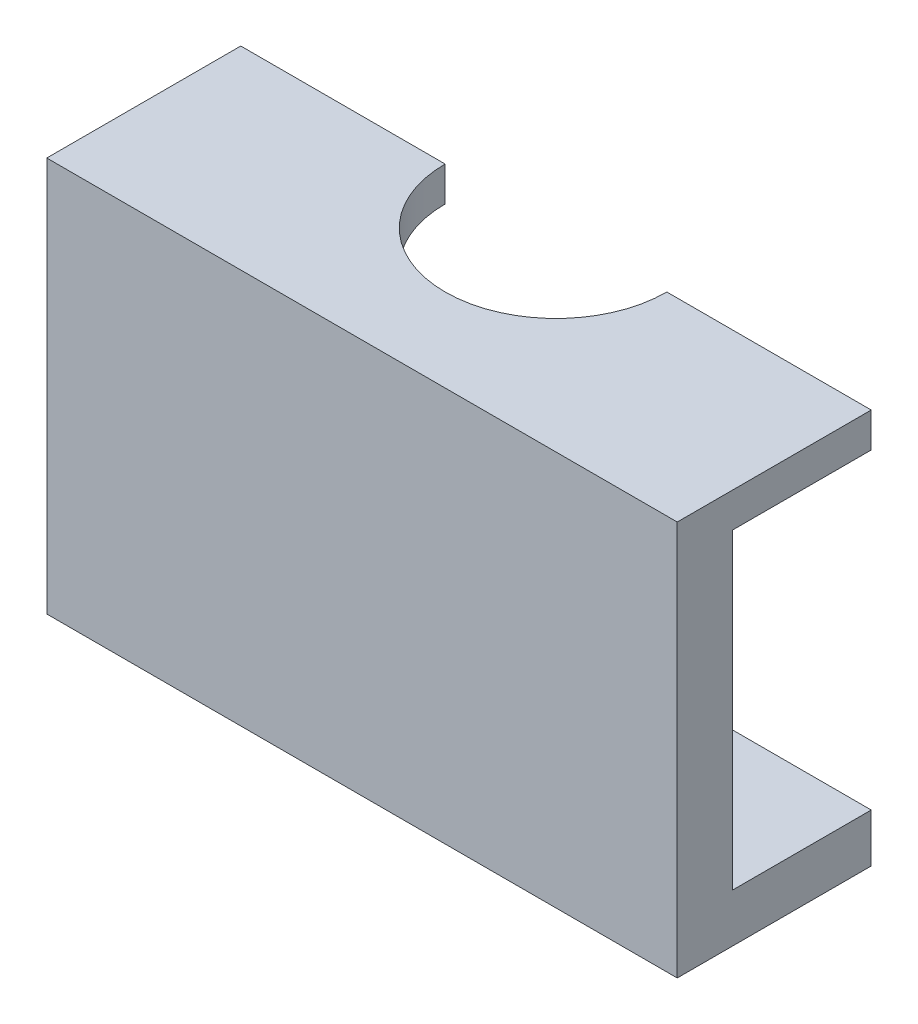
SolidWorks part; units mm, degrees
ref_plane "Front Plane" through (0, 0, 0) normal (0, 0, 1) x (1, 0, 0)
ref_plane "Top Plane" through (0, 0, 0) normal (0, 1, 0) x (1, 0, 0)
ref_plane "Right Plane" through (0, 0, 0) normal (1, 0, 0) x (0, 0, -1)
sketch "Sketch1" plane through (0, 0, 0) normal (0, 0, 1) x (1, 0, 0)
  line L1 (0, 0) -> (45.5, 0)
  line L2 (0, 0) -> (0, 28.5)
  line L3 (0, 28.5) -> (45.5, 28.5)
  line L4 (45.5, 0) -> (45.5, 28.5)
  point P5 (38, 33.2825)
  dimension "D1" = 45.5
  dimension "D2" = 28.5
extrude "Boss-Extrude1" add sketch "Sketch1" along normal blind 14
sketch "Sketch2" plane through (0, 28.5, 0) normal (0, 1, 0) x (1, 0, 0)
  line L0 (45.5, 0) -> (0, 0) construction
  circle A0 centre (22.75, 0) radius 8
  dimension "D1" = 16
extrude "Cut-Extrude1" cut sketch "Sketch2" against normal blind 30
sketch "Sketch3" plane through (0, 0, 0) normal (0, -1, 0) x (1, 0, 0)
  circle A0 centre (22.75, 0) radius 11.1
  dimension "D1" = 22.2
extrude "Cut-Extrude2" cut sketch "Sketch3" against normal offset from surface (26 mm away) 2.5 up to face at (22.75, 28.5, 6)
sketch "Sketch4" plane through (45.5, 0, 0) normal (1, 0, 0) x (0, 0, -1)
  line L0 (0, 0) -> (0, 28.5) construction
  line L1 (0, 26) -> (-9.9973, 26)
  line L2 (0, 26) -> (0, 3.5)
  line L3 (0, 3.5) -> (-9.9973, 3.5)
  line L4 (-9.9973, 26) -> (-9.9973, 3.5)
  line L5 (-8, 26) -> (0, 26) construction
  line L6 (-14, 0) -> (0, 0) construction
  dimension "D1" = 3.5
  dimension "D2" = 9.9973
extrude "Cut-Extrude3" cut sketch "Sketch4" against normal through all
